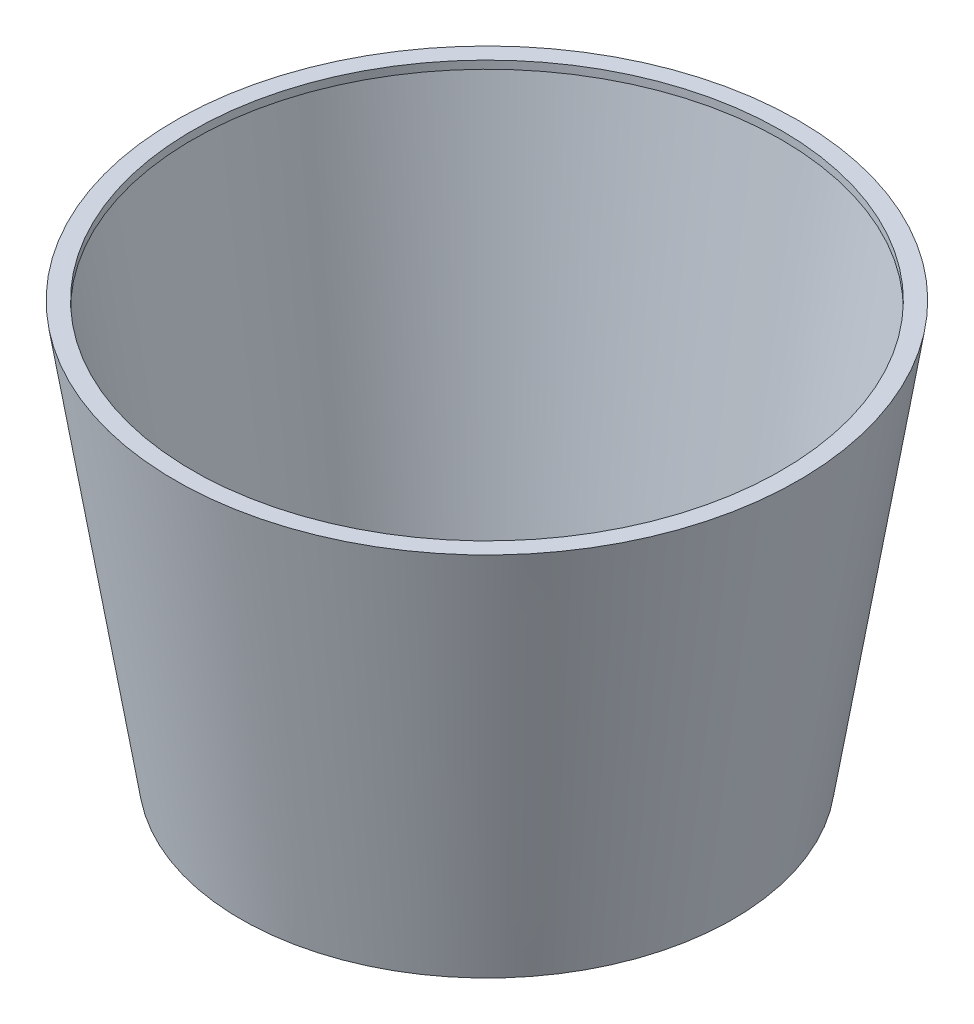
SolidWorks part; units mm, degrees
material "ABS"
ref_plane "Front Plane" through (0, 0, 0) normal (0, 0, 1) x (1, 0, 0)
ref_plane "Top Plane" through (0, 0, 0) normal (0, 1, 0) x (1, 0, 0)
ref_plane "Right Plane" through (0, 0, 0) normal (1, 0, 0) x (0, 0, -1)
sketch "Sketch1" plane through (0, 0, 0) normal (0, 0, 1) x (1, 0, 0)
  line L0 (0, 0) -> (0, 69.3738) construction
  line L1 (0, 0) -> (30.1625, 0)
  line L2 (30.1625, 0) -> (38.1, 50)
  line L3 (38.1, 50) -> (37.1, 50)
  dimension "D1" = 30.1625
  dimension "D2" = 38.1
  dimension "D3" = 50
  dimension "D6" = 1
revolve "Revolve-Thin3" add sketch "Sketch1" angle 360 about L0
